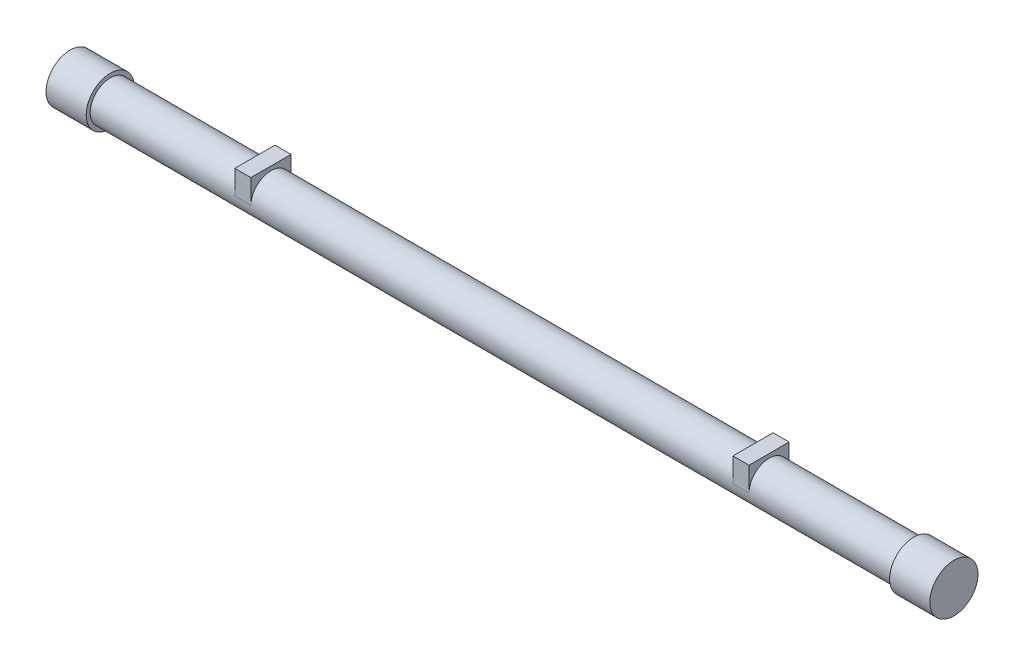
SolidWorks part; units mm, degrees
ref_plane "Front Plane" through (0, 0, 0) normal (0, 0, 1) x (1, 0, 0)
ref_plane "Top Plane" through (0, 0, 0) normal (0, 1, 0) x (1, 0, 0)
ref_plane "Right Plane" through (0, 0, 0) normal (1, 0, 0) x (0, 0, -1)
sketch "Sketch1" plane through (0, 0, 0) normal (1, 0, 0) x (0, 0, -1)
  circle A0 centre (0, 0) radius 12.5
  dimension "D1" = 25
extrude "Boss-Extrude1" add sketch "Sketch1" along normal blind 550
sketch "Sketch2" plane through (550, 0, 0) normal (1, 0, 0) x (0, 0, -1)
  circle A0 centre (0, 0) radius 15
  dimension "D1" = 30
extrude "Boss-Extrude2" add sketch "Sketch2" against normal blind 25
sketch "Sketch3" plane through (0, 0, 0) normal (-1, 0, 0) x (0, 0, 1)
  circle A0 centre (0, 0) radius 15
  dimension "D1" = 30
extrude "Boss-Extrude3" add sketch "Sketch3" against normal blind 25
sketch "Sketch4" plane through (0, 0, 0) normal (0, 1, 0) x (1, 0, 0)
  line L0 (25, 0) -> (80, 0) construction
  line L1 (25, -12.5) -> (25, 12.5) construction
  line L2 (525, 0) -> (464.4016, 0) construction
  line L3 (525, 15) -> (525, -15) construction
  line L4 (85, 0) -> (115, 0) construction
  line L5 (525, 12.5) -> (25, 12.5) construction
  line L6 (115, 12.5) -> (125, 12.5)
  line L7 (115, 12.5) -> (115, -12.5)
  line L8 (115, -12.5) -> (125, -12.5)
  line L9 (125, 12.5) -> (125, -12.5)
  line L10 (25, -12.5) -> (525, -12.5) construction
  line L11 (275, 12.5) -> (275, -12.5) construction
  line L12 (435, -12.5) -> (425, -12.5)
  line L13 (435, 12.5) -> (435, -12.5)
  line L14 (435, 12.5) -> (425, 12.5)
  line L15 (425, 12.5) -> (425, -12.5)
  line L16 (465, 0) -> (435, 0) construction
  line L17 (525, 0) -> (470, 0) construction
  dimension "D1" = 55
  dimension "D2" = 30
  dimension "D3" = 5
  dimension "D4" = 10
  dimension "D5" = 30
extrude "Boss-Extrude4" add sketch "Sketch4" along normal blind 15
